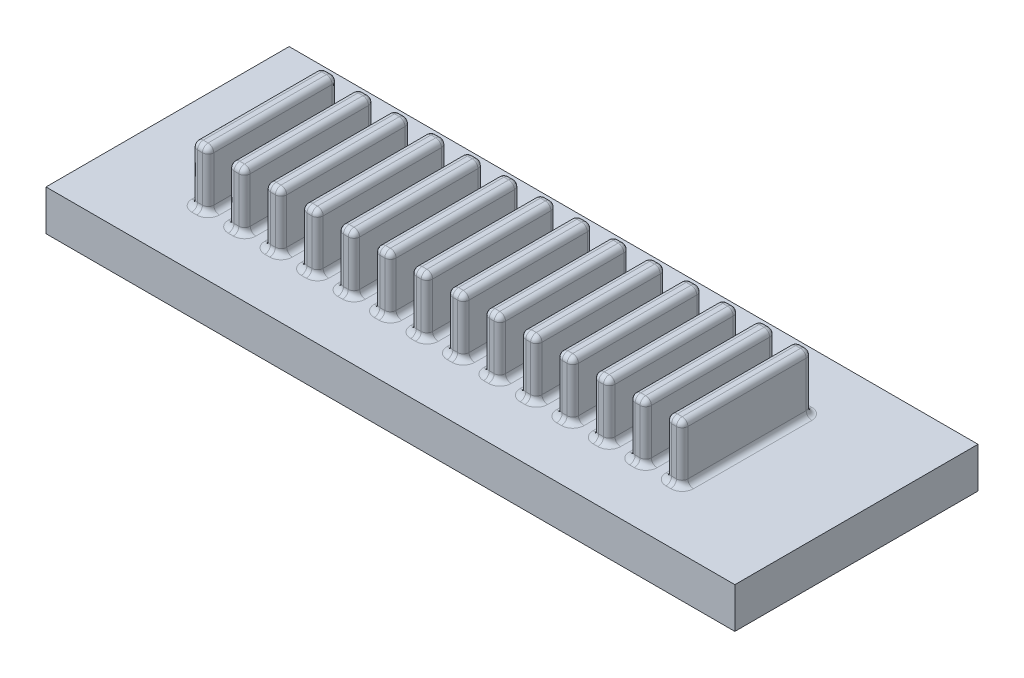
SolidWorks part; units mm, degrees
ref_plane "Front" through (0, 0, 0) normal (0, 0, 1) x (1, 0, 0)
ref_plane "Top" through (0, 0, 0) normal (0, 1, 0) x (1, 0, 0)
ref_plane "Right" through (0, 0, 0) normal (1, 0, 0) x (0, 0, -1)
sketch "Sketch1" plane through (0, 0, 0) normal (0, 1, 0) x (1, 0, 0)
  line L1 (0, 0) -> (85, 0)
  line L2 (0, 0) -> (0, 30)
  line L3 (0, 30) -> (85, 30)
  line L4 (85, 0) -> (85, 30)
  dimension "D1" = 30
  dimension "D2" = 85
extrude "Boss-Extrude1" add sketch "Sketch1" along normal blind 5
sketch "Sketch2" plane through (0, 5, 0) normal (0, 1, 0) x (1, 0, 0)
  line L0 (0, 30) -> (0, 0) construction
  line L1 (11, 23) -> (13, 23)
  line L2 (11, 23) -> (11, 7)
  line L3 (11, 7) -> (13, 7)
  line L4 (13, 23) -> (13, 7)
  line L5 (85, 30) -> (0, 30) construction
  line L58 (15.5, 23) -> (15.5, 7)
  line L59 (17.5, 23) -> (17.5, 7)
  line L60 (15.5, 7) -> (17.5, 7)
  line L61 (15.5, 23) -> (17.5, 23)
  line L62 (20, 23) -> (20, 7)
  line L63 (22, 23) -> (22, 7)
  line L64 (20, 7) -> (22, 7)
  line L65 (20, 23) -> (22, 23)
  line L66 (24.5, 23) -> (24.5, 7)
  line L67 (26.5, 23) -> (26.5, 7)
  line L68 (24.5, 7) -> (26.5, 7)
  line L69 (24.5, 23) -> (26.5, 23)
  line L70 (29, 23) -> (29, 7)
  line L71 (31, 23) -> (31, 7)
  line L72 (29, 7) -> (31, 7)
  line L73 (29, 23) -> (31, 23)
  line L74 (33.5, 23) -> (33.5, 7)
  line L75 (35.5, 23) -> (35.5, 7)
  line L76 (33.5, 7) -> (35.5, 7)
  line L77 (33.5, 23) -> (35.5, 23)
  line L78 (38, 23) -> (38, 7)
  line L79 (40, 23) -> (40, 7)
  line L80 (38, 7) -> (40, 7)
  line L81 (38, 23) -> (40, 23)
  line L82 (42.5, 23) -> (42.5, 7)
  line L83 (44.5, 23) -> (44.5, 7)
  line L84 (42.5, 7) -> (44.5, 7)
  line L85 (42.5, 23) -> (44.5, 23)
  line L86 (47, 23) -> (47, 7)
  line L87 (49, 23) -> (49, 7)
  line L88 (47, 7) -> (49, 7)
  line L89 (47, 23) -> (49, 23)
  line L90 (51.5, 23) -> (51.5, 7)
  line L91 (53.5, 23) -> (53.5, 7)
  line L92 (51.5, 7) -> (53.5, 7)
  line L93 (51.5, 23) -> (53.5, 23)
  line L94 (56, 23) -> (56, 7)
  line L95 (58, 23) -> (58, 7)
  line L96 (56, 7) -> (58, 7)
  line L97 (56, 23) -> (58, 23)
  line L98 (60.5, 23) -> (60.5, 7)
  line L99 (62.5, 23) -> (62.5, 7)
  line L100 (60.5, 7) -> (62.5, 7)
  line L101 (60.5, 23) -> (62.5, 23)
  line L102 (65, 23) -> (65, 7)
  line L103 (67, 23) -> (67, 7)
  line L104 (65, 7) -> (67, 7)
  line L105 (65, 23) -> (67, 23)
  line L106 (69.5, 23) -> (69.5, 7)
  line L107 (71.5, 23) -> (71.5, 7)
  line L108 (69.5, 7) -> (71.5, 7)
  line L109 (69.5, 23) -> (71.5, 23)
  dimension "D1" = 16
  dimension "D2" = 2
  dimension "D3" = 11
  dimension "D4" = 7
  dimension "D5" = 14
extrude "Boss-Extrude2" add sketch "Sketch2" along normal blind 7
fillet "Fillet1" radius 0.7 44 edges at (13, 8.5, -7) (13, 5, -15) (12, 12, -7) (26.5, 8.5, -7) (26.5, 5, -15) (25.5, 12, -7) (24.5, 12, -15) (16.5, 5, -23) (17.5, 12, -15) (21, 5, -23) (22, 8.5, -23) (30, 5, -7) (31, 8.5, -23) (31, 5, -15) (31, 12, -15) (30, 12, -23) (33.5, 8.5, -23) (33.5, 12, -15) (38, 8.5, -23) (40, 12, -15) (39, 12, -23) (43.5, 5, -7) (44.5, 12, -15) (42.5, 12, -15) (48, 5, -23) (47, 8.5, -23) (47, 8.5, -7) (48, 5, -7) (49, 8.5, -7) (52.5, 5, -23) (52.5, 5, -7) (52.5, 12, -7) (56, 8.5, -7) (58, 8.5, -23) (60.5, 8.5, -7) (61.5, 5, -7) (62.5, 5, -15) (61.5, 12, -7) (66, 5, -23) (66, 5, -7) (65, 12, -15) (70.5, 5, -7) (71.5, 8.5, -7) (70.5, 12, -7)
